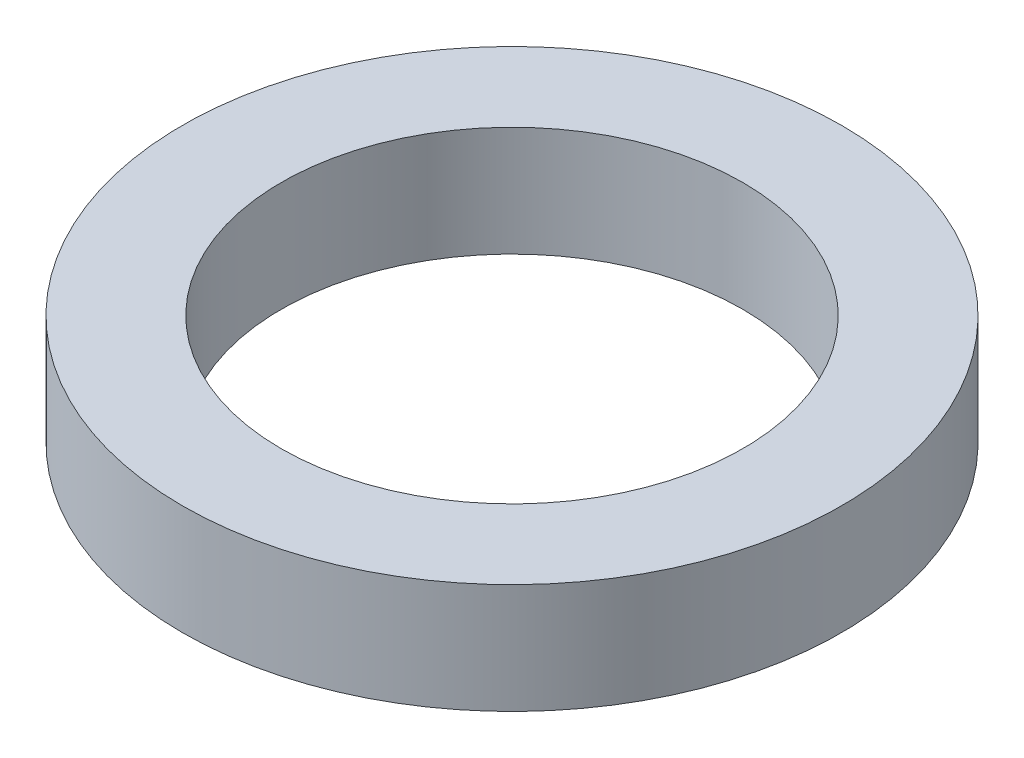
SolidWorks part; units mm, degrees
material "ABS"
ref_plane "正面" through (0, 0, 0) normal (0, 0, 1) x (1, 0, 0)
ref_plane "平面" through (0, 0, 0) normal (0, 1, 0) x (1, 0, 0)
ref_plane "右側面" through (0, 0, 0) normal (1, 0, 0) x (0, 0, -1)
sketch "ｽｹｯﾁ1" plane through (0, 0, 0) normal (0, 1, 0) x (1, 0, 0)
  circle A0 centre (0, 0) radius 2.1
  circle A1 centre (0, 0) radius 3
  dimension "D1" = 6
  dimension "D2" = 4.2
extrude "ﾎﾞｽ - 押し出し1" add sketch "ｽｹｯﾁ1" along normal blind 1
